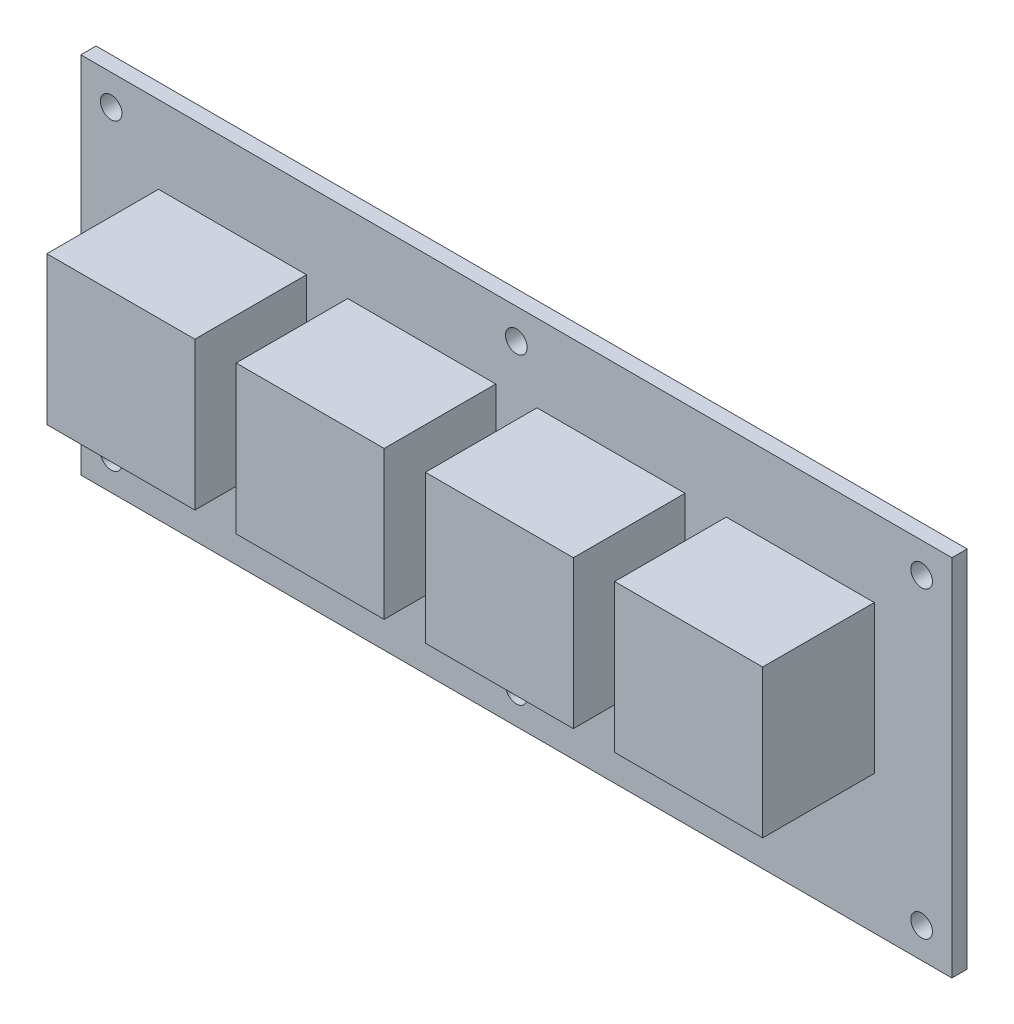
SolidWorks part; units mm, degrees
ref_plane "Front Plane" through (0, 0, 0) normal (0, 0, 1) x (1, 0, 0)
ref_plane "Top Plane" through (0, 0, 0) normal (0, 1, 0) x (1, 0, 0)
ref_plane "Right Plane" through (0, 0, 0) normal (1, 0, 0) x (0, 0, -1)
sketch "Sketch1" plane through (0, 0, 0) normal (0, 0, 1) x (1, 0, 0)
  line L0 (0, 0) -> (91.186, 0)
  line L1 (91.186, 0) -> (91.186, 38.1)
  line L2 (91.186, 38.1) -> (0, 38.1)
  line L3 (0, 38.1) -> (0, 0)
extrude "BOARD" add sketch "Sketch1" along normal blind 1.5921 separate body
ref_plane "Plane1" through (0, 0, 1.5921) normal (0, 0, 1) x (1, 0, 0)
sketch "Sketch2" plane through (0, 0, 0) normal (0, 0, 1) x (1, 0, 0)
  line L0 (60.7568, 13.3604) -> (60.7568, 0.5334)
  line L1 (60.7568, 0.5334) -> (76.2508, 0.5334)
  line L2 (76.2508, 0.5334) -> (76.2508, 13.3604)
  line L3 (76.2508, 13.3604) -> (60.7568, 13.3604)
sketch "Sketch3" plane through (0, 0, 1.5921) normal (0, 0, 1) x (1, 0, 0)
  line L0 (67.564, 14.478) -> (67.564, 29.972)
  line L1 (67.564, 29.972) -> (83.058, 29.972)
  line L2 (83.058, 29.972) -> (83.058, 14.478)
  line L3 (83.058, 14.478) -> (67.564, 14.478)
extrude "MX1A-1" add sketch "Sketch3" along normal blind 11.684 separate body
sketch "Sketch4" plane through (0, 0, 1.5921) normal (0, 0, 1) x (1, 0, 0)
  line L0 (47.752, 14.478) -> (47.752, 29.972)
  line L1 (47.752, 29.972) -> (63.246, 29.972)
  line L2 (63.246, 29.972) -> (63.246, 14.478)
  line L3 (63.246, 14.478) -> (47.752, 14.478)
extrude "MX1A-2" add sketch "Sketch4" along normal blind 11.684 separate body
sketch "Sketch5" plane through (0, 0, 1.5921) normal (0, 0, 1) x (1, 0, 0)
  line L0 (27.94, 14.478) -> (27.94, 29.972)
  line L1 (27.94, 29.972) -> (43.434, 29.972)
  line L2 (43.434, 29.972) -> (43.434, 14.478)
  line L3 (43.434, 14.478) -> (27.94, 14.478)
extrude "MX1A-3" add sketch "Sketch5" along normal blind 11.684 separate body
sketch "Sketch6" plane through (0, 0, 1.5921) normal (0, 0, 1) x (1, 0, 0)
  line L0 (8.128, 14.478) -> (8.128, 29.972)
  line L1 (8.128, 29.972) -> (23.622, 29.972)
  line L2 (23.622, 29.972) -> (23.622, 14.478)
  line L3 (23.622, 14.478) -> (8.128, 14.478)
extrude "MX1A-4" add sketch "Sketch6" along normal blind 11.684 separate body
sketch "Sketch7" plane through (0, 0, 1.5921) normal (0, 0, 1) x (1, 0, 0)
  circle A0 centre (88.011, 34.925) radius 1.1303
  circle A1 centre (88.011, 3.175) radius 1.1303
  circle A2 centre (45.593, 34.925) radius 1.1303
  circle A3 centre (45.593, 3.175) radius 1.1303
  circle A4 centre (3.175, 34.925) radius 1.1303
  circle A5 centre (3.175, 3.175) radius 1.1303
extrude "Cut-Extrude1" cut sketch "Sketch7" against normal blind 10
sketch "Sketch9" plane through (0, 0, 13.2761) normal (0, 0, 1) x (1, 0, 0)
  circle A0 centre (15.875, 22.225) radius 7.747
